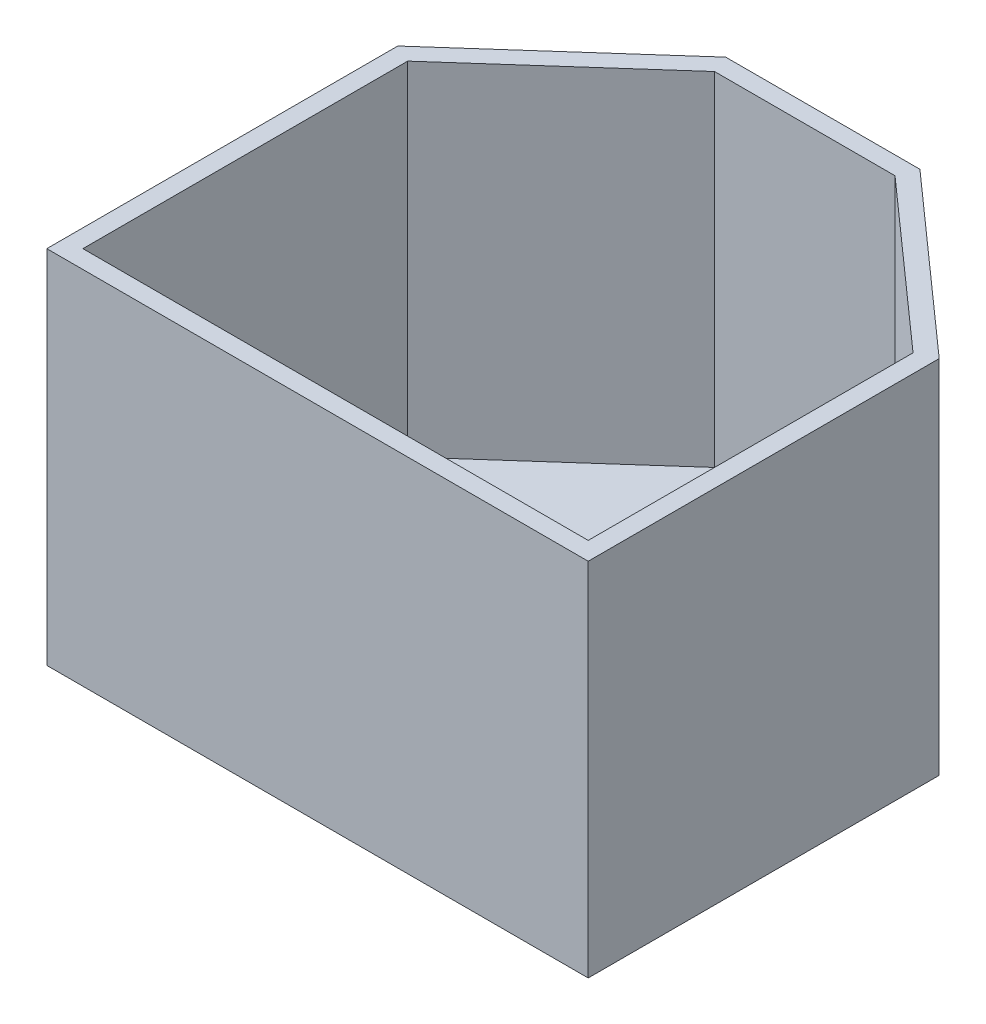
SolidWorks part; units mm, degrees
ref_plane "Front Plane" through (0, 0, 0) normal (0, 0, 1) x (1, 0, 0)
ref_plane "Top Plane" through (0, 0, 0) normal (0, 1, 0) x (1, 0, 0)
ref_plane "Right Plane" through (0, 0, 0) normal (1, 0, 0) x (0, 0, -1)
sketch "Sketch2" plane through (0, 0, 0) normal (0, 1, 0) x (1, 0, 0)
  line L0 (12.7, 33.02) -> (35.56, 33.02) construction
  line L1 (-35.56, 33.02) -> (-12.7, 33.02) construction
  line L2 (35.56, 33.02) -> (35.56, 12.7) construction
  line L3 (35.56, -33.02) -> (-35.56, -33.02)
  line L4 (-35.56, 33.02) -> (-35.56, 12.7) construction
  line L5 (-12.7, 33.02) -> (-35.56, 12.7)
  line L6 (12.7, 33.02) -> (35.56, 12.7)
  line L7 (-12.7, 33.02) -> (12.7, 33.02)
  line L8 (-35.56, 12.7) -> (-35.56, -33.02)
  line L9 (35.56, 12.7) -> (35.56, -33.02)
  line L16 (-13.6657, 35.56) -> (-38.1, 13.8406)
  line L17 (-38.1, 13.8406) -> (-38.1, -35.56)
  line L18 (38.1, -35.56) -> (-38.1, -35.56)
  line L19 (38.1, 13.8406) -> (38.1, -35.56)
  line L20 (13.6657, 35.56) -> (38.1, 13.8406)
  line L21 (-13.6657, 35.56) -> (13.6657, 35.56)
  point P3 (-35.56, 12.7)
  point P7 (0, -33.02)
  point P9 (35.56, 12.7)
  point P10 (12.7, 33.02)
  point P11 (-12.7, 33.02)
  dimension "D1" = 66.04
  dimension "D2" = 71.12
  dimension "D3" = 20.32
  dimension "D4" = 12.7
  dimension "D5" = 12.7
  dimension "D6" = 33.02
  dimension "D7" = 2.54
extrude "Boss-Extrude1" add sketch "Sketch2" along normal mid plane 50.8 contours L9 L6 L7 L5 L8 L3 | L20 L21 L16 L17 L18 L19 L6 L9 L3 L8 L5 L7
shell "Shell1" thickness 2.54
